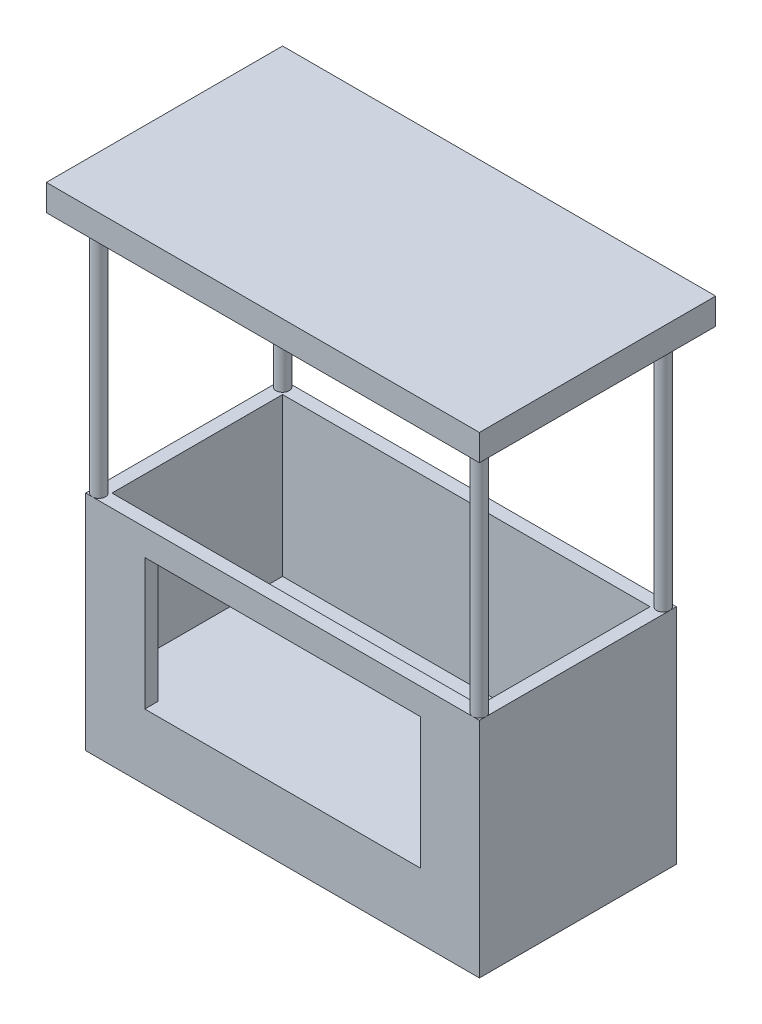
SolidWorks part; units mm, degrees
ref_plane "前视基准面" through (0, 0, 0) normal (0, 0, 1) x (1, 0, 0)
ref_plane "上视基准面" through (0, 0, 0) normal (0, 1, 0) x (1, 0, 0)
ref_plane "右视基准面" through (0, 0, 0) normal (1, 0, 0) x (0, 0, -1)
sketch "草图1" plane through (0, 0, 0) normal (0, 1, 0) x (1, 0, 0)
  line L0 (0, 0) -> (60, 0)
  line L1 (0, 0) -> (0, 30)
  line L2 (0, 30) -> (60, 30)
  line L3 (60, 30) -> (60, 0)
  dimension "D1" = 60
  dimension "D2" = 30
extrude "凸台-拉伸1" add sketch "草图1" along normal blind 10
sketch "草图2" plane through (0, 10, 0) normal (0, 1, 0) x (1, 0, 0)
  line L0 (60, 0) -> (51, 0)
  line L1 (0, 0) -> (60, 0) construction
  line L2 (51, 0) -> (51, 2)
  line L3 (51, 2) -> (58, 2)
  line L4 (58, 2) -> (58, 28)
  line L5 (58, 28) -> (2, 28)
  line L6 (2, 28) -> (2, 2)
  line L7 (2, 2) -> (9, 2)
  line L8 (9, 2) -> (9, 0)
  line L9 (9, 0) -> (0, 0)
  line L10 (0, 0) -> (0, 30)
  line L11 (0, 30) -> (60, 30)
  line L12 (60, 30) -> (60, 0)
  dimension "D1" = 9
  dimension "D2" = 9
  dimension "D3" = 2
  dimension "D4" = 2
  dimension "D5" = 2
  dimension "D6" = 2
  dimension "D7" = 2
extrude "凸台-拉伸2" add sketch "草图2" along normal blind 20
sketch "草图3" plane through (0, 30, 0) normal (0, 1, 0) x (1, 0, 0)
  line L0 (60, 0) -> (60, 30) construction
  line L1 (0, 30) -> (0, 0) construction
  line L2 (60, 30) -> (0, 30) construction
  line L3 (60, 0) -> (60, 30)
  line L4 (0, 30) -> (0, 0)
  line L5 (60, 30) -> (0, 30)
  line L6 (60, 0) -> (0, 0)
  line L7 (58, 28) -> (58, 2) construction
  line L8 (2, 2) -> (2, 28) construction
  line L9 (2, 28) -> (58, 28) construction
  line L10 (58, 28) -> (58, 2)
  line L11 (2, 2) -> (2, 28)
  line L12 (2, 28) -> (58, 28)
  line L13 (2, 2) -> (58, 2)
extrude "凸台-拉伸3" add sketch "草图3" along normal blind 4
sketch "草图4" plane through (0, 34, 0) normal (0, 1, 0) x (1, 0, 0)
  line L0 (0, 30) -> (2, 28) construction
  line L1 (2, 2) -> (0, 0) construction
  line L2 (60, 30) -> (58, 28) construction
  line L3 (58, 2) -> (60, 0) construction
  circle A1 centre (1, 29) radius 1
  circle A2 centre (1, 1) radius 1
  circle A3 centre (59, 29) radius 1
  circle A4 centre (59, 1) radius 1
  dimension "D1" = 2
  dimension "D2" = 2
  dimension "D3" = 2
  dimension "D4" = 2
extrude "凸台-拉伸4" add sketch "草图4" along normal blind 37
sketch "草图5" plane through (0, 71, 0) normal (0, 1, 0) x (1, 0, 0)
  line L0 (-3, 33) -> (-3, -3)
  line L1 (-3, -3) -> (63, -3)
  line L2 (63, -3) -> (63, 33)
  line L3 (63, 33) -> (-3, 33)
  line L4 (59, 30) -> (1, 30) construction
  line L5 (0, 29) -> (0, 1) construction
  line L6 (1, 0) -> (59, 0) construction
  line L7 (60, 1) -> (60, 29) construction
  dimension "D1" = 3
  dimension "D2" = 3
  dimension "D3" = 3
  dimension "D4" = 3
extrude "凸台-拉伸5" add sketch "草图5" along normal blind 4
sketch "草图6" plane through (0, 10, 0) normal (0, 1, 0) x (1, 0, 0)
  circle A0 centre (52.583, 22.9074) radius 5
  point P2 (51.6537, 22.7805)
  point P3 (52.583, 22.9074)
  dimension "D1" = 10
extrude "切除-拉伸1" cut sketch "草图6" against normal up to next
